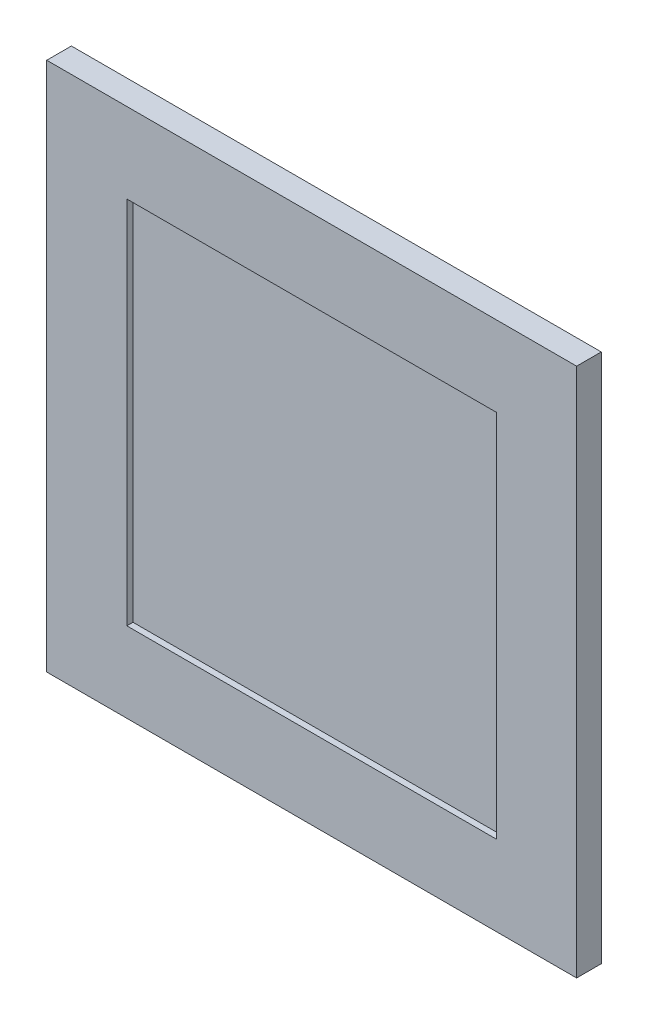
SolidWorks part; units mm, degrees
ref_plane "정면" through (0, 0, 0) normal (0, 0, 1) x (1, 0, 0)
ref_plane "윗면" through (0, 0, 0) normal (0, 1, 0) x (1, 0, 0)
ref_plane "우측면" through (0, 0, 0) normal (1, 0, 0) x (0, 0, -1)
sketch "스케치2" plane through (0, 0, 0) normal (0, 0, 1) x (1, 0, 0)
  line L1 (-215, 215) -> (215, 215)
  line L2 (-215, 215) -> (-215, -215)
  line L3 (-215, -215) -> (215, -215)
  line L4 (215, 215) -> (215, -215)
  line L5 (-215, 215) -> (215, -215) construction
  line L6 (-215, -215) -> (215, 215) construction
  point P0 (0, 0)
  dimension "92" = 430
  dimension "D2" = 430
extrude "보스-돌출1" add sketch "스케치2" along normal blind 20
sketch "스케치3" plane through (0, 0, 20) normal (0, 0, 1) x (1, 0, 0)
  line L5 (215, 215) -> (-215, 215) construction
  line L6 (-150, 150) -> (150, 150)
  line L7 (-150, 150) -> (-150, -150)
  line L9 (-150, -150) -> (150, -150)
  line L10 (150, 150) -> (150, -150)
  line L11 (-150, 150) -> (150, -150) construction
  line L12 (-150, -150) -> (150, 150) construction
  line L13 (215, -215) -> (215, 215) construction
  point P0 (0, 0)
  dimension "D1" = 65
  dimension "D2" = 65
extrude "컷-돌출1" cut sketch "스케치3" against normal blind 5
